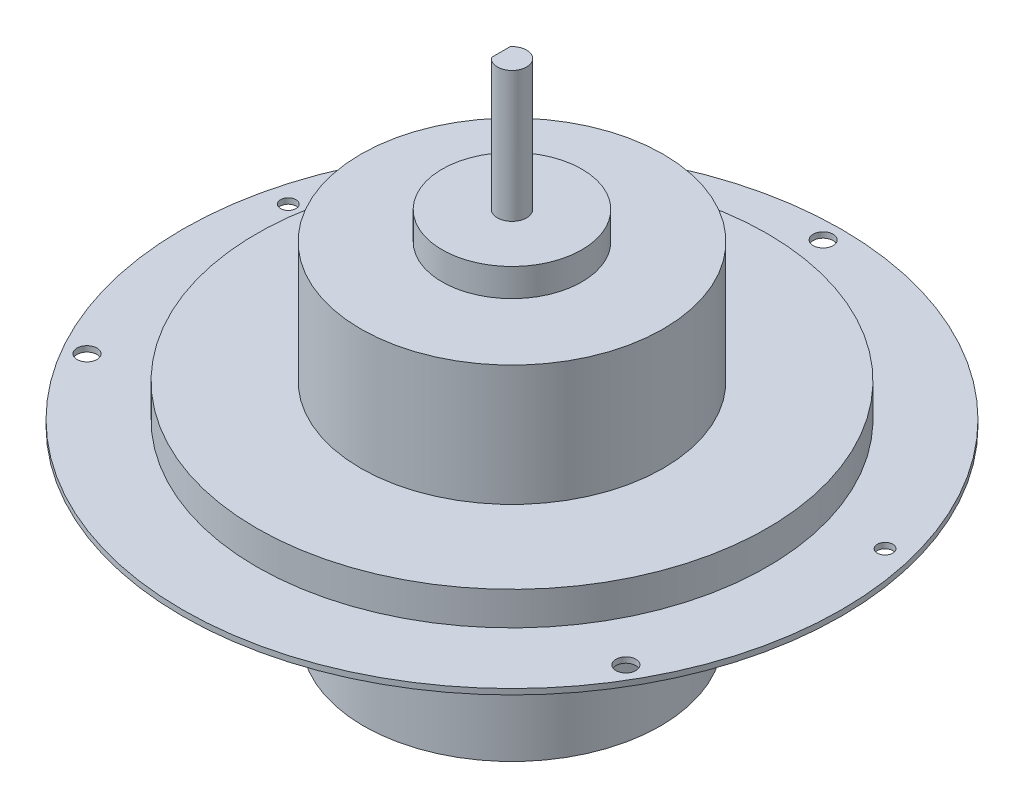
SolidWorks part; units mm, degrees
ref_plane "Front Plane" through (0, 0, 0) normal (0, 0, 1) x (1, 0, 0)
ref_plane "Top Plane" through (0, 0, 0) normal (0, 1, 0) x (1, 0, 0)
ref_plane "Right Plane" through (0, 0, 0) normal (1, 0, 0) x (0, 0, -1)
sketch "Sketch1" plane through (0, 0, 0) normal (0, 1, 0) x (1, 0, 0)
  circle A0 centre (0, 0) radius 90.17
  dimension "D1" = 180.34
extrude "Boss-Extrude1" add sketch "Sketch1" along normal mid plane 1.524
sketch "Sketch2" plane through (0, 0.762, 0) normal (0, 1, 0) x (1, 0, 0)
  circle A0 centre (0, 0) radius 69.85
  dimension "D1" = 139.7
extrude "Boss-Extrude2" add sketch "Sketch2" along normal blind 9.144
sketch "Sketch3" plane through (0, 9.906, 0) normal (0, 1, 0) x (1, 0, 0)
  circle A0 centre (0, 0) radius 41.402
  dimension "D1" = 82.804
extrude "Boss-Extrude3" add sketch "Sketch3" along normal blind 33.02
sketch "Sketch4" plane through (0, 42.926, 0) normal (0, 1, 0) x (1, 0, 0)
  circle A0 centre (0, 0) radius 19.1262
  dimension "D1" = 38.2524
extrude "Boss-Extrude4" add sketch "Sketch4" along normal blind 7.62
sketch "Sketch5" plane through (0, 50.546, 0) normal (0, 1, 0) x (1, 0, 0)
  circle A0 centre (0, 0) radius 4.0005
  dimension "D1" = 8.001
extrude "Boss-Extrude5" add sketch "Sketch5" along normal blind 35.7632
sketch "Sketch6" plane through (0, 86.3092, 0) normal (0, 1, 0) x (1, 0, 0)
  line L0 (-38.4806, 0) -> (38.4806, 0) construction
  line L1 (0, -32.9382) -> (0, 32.9382) construction
  line L2 (-3.0734, -2.6797) -> (-3.0734, 2.6797)
  arc A0 (-3.0734, 2.6797) -> (-3.0734, -2.6797) centre (0, 0) ccw
  point P5 (0, 0)
  point P9 (0, 0)
  point P12 (-3.0734, 0)
  dimension "D1" = 5.3594
  dimension "D2" = 3.0734
extrude "Cut-Extrude1" cut sketch "Sketch6" against normal blind 24.4602
sketch "Sketch7" plane through (0, 0.762, 0) normal (0, 1, 0) x (1, 0, 0)
  line L0 (-151.3915, 0) -> (151.3915, 0) construction
  line L1 (0, -112.0514) -> (0, 112.0514) construction
  circle A0 centre (0, 85.1408) radius 2.7178
  circle A1 centre (0, 0) radius 90.17 construction
  circle A2 centre (0, 0) radius 85.1408 construction
  circle A3 centre (73.7341, -42.5704) radius 2.7178
  circle A4 centre (0, 0) radius 85.1408 construction
  circle A5 centre (-73.7341, -42.5704) radius 2.7178
  circle A6 centre (0, 0) radius 85.1408 construction
  point P7 (0, 0)
  point P11 (0, 0)
  point P26 (0, 0)
  dimension "D1" = 5.4356
  dimension "D2" = 85.1408
  dimension "D3" = 3
extrude "Cut-Extrude2" cut sketch "Sketch7" against normal blind 6.35
sketch "Sketch8" plane through (0, 0.762, 0) normal (0, 1, 0) x (1, 0, 0)
  line L0 (-152.3855, 0) -> (152.3855, 0) construction
  line L1 (0, -104.2801) -> (0, 104.2801) construction
  circle A0 centre (-81.6579, 20.4333) radius 2.1209
  circle A1 centre (-73.7341, -42.5704) radius 2.7178 construction
  circle A2 centre (81.6579, 20.4333) radius 2.1209
  point P6 (0, 0)
  point P10 (0, 0)
  dimension "D1" = 4.2418
  dimension "D2" = 63.5
  dimension "D3" = 84.1756
extrude "Cut-Extrude3" cut sketch "Sketch8" against normal blind 6.35
sketch "Sketch9" plane through (0, -0.762, 0) normal (0, -1, 0) x (1, 0, 0)
  circle A0 centre (0, 0) radius 40.64
  dimension "D1" = 81.28
extrude "Boss-Extrude6" add sketch "Sketch9" along normal blind 50.8
